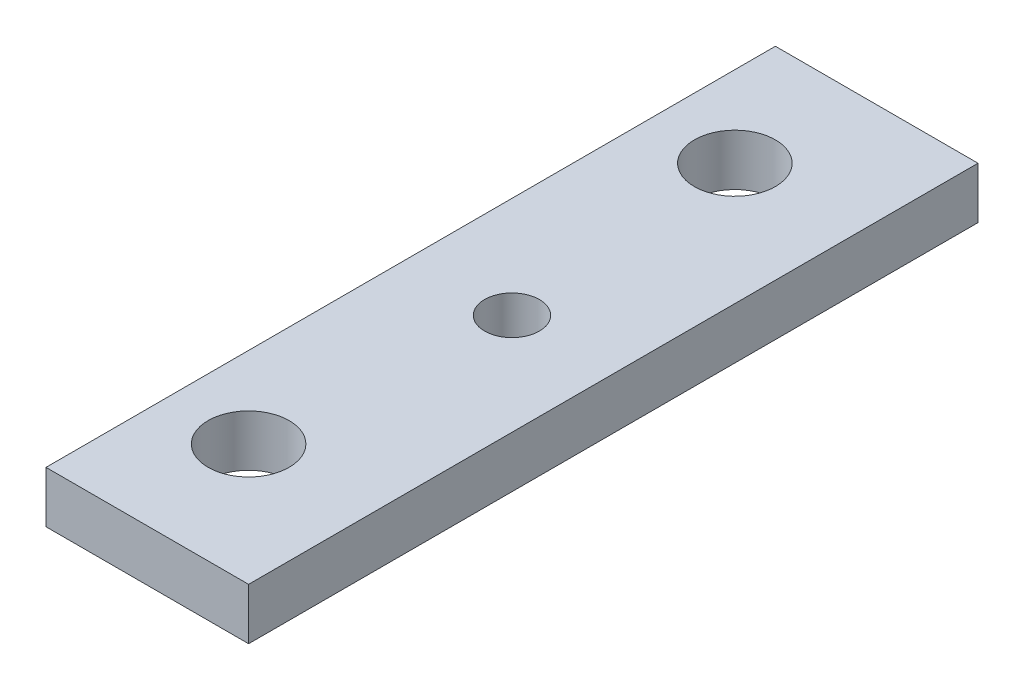
SolidWorks part; units mm, degrees
material "Aleación 1060"
ref_plane "Alzado" through (0, 0, 0) normal (0, 0, 1) x (1, 0, 0)
ref_plane "Planta" through (0, 0, 0) normal (0, 1, 0) x (1, 0, 0)
ref_plane "Vista lateral" through (0, 0, 0) normal (1, 0, 0) x (0, 0, -1)
sketch "Croquis1" plane through (0, 0, 0) normal (0, 1, 0) x (1, 0, 0)
  line L0 (-5, 129.5738) -> (-5, -125.7049) construction
  line L1 (-25, -90) -> (25, -90)
  line L2 (-25, -90) -> (-25, 90)
  line L3 (-25, 90) -> (25, 90)
  line L4 (25, -90) -> (25, 90)
  line L5 (-25, -90) -> (25, 90) construction
  line L6 (-25, 90) -> (25, -90) construction
  circle A0 centre (-5, 60) radius 10
  circle A1 centre (-5, -60) radius 10
  circle A2 centre (0, 0) radius 6.7597
  point P0 (0, 0)
  dimension "D4" = 20
  dimension "D6" = 20
  dimension "D1" = 180
  dimension "D2" = 50
  dimension "D3" = 30
  dimension "D5" = 60
  dimension "D7" = 60
extrude "Saliente-Extruir1" add sketch "Croquis1" along normal blind 12.7
equation "\"D6@Croquis1\"=\"D4@Croquis1\""
equation "\"D7@Croquis1\"=\"D5@Croquis1\""
